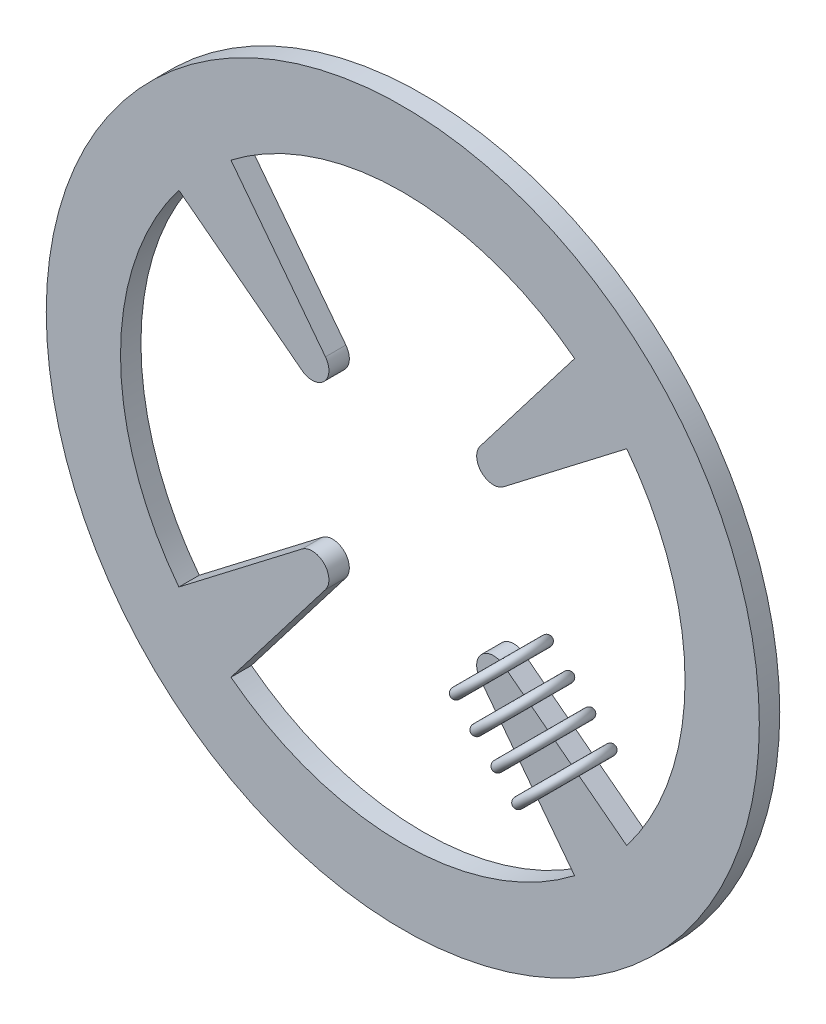
SolidWorks part; units mm, degrees
other "標示1"
sketch "草圖65"
ref_plane "前基準面" through (0, 0, 0) normal (0, 0, 1) x (1, 0, 0)
ref_plane "上基準面" through (0, 0, 0) normal (0, 1, 0) x (1, 0, 0)
ref_plane "右基準面" through (0, 0, 0) normal (1, 0, 0) x (0, 0, -1)
sketch "草圖1" plane through (0, 0, 0) normal (0, 0, 1) x (1, 0, 0)
  circle A0 centre (0, 0) radius 0.96
  circle A1 centre (0, 0) radius 0.76
extrude "填料-伸長1" add sketch "草圖1" along normal blind 0.055
sketch "草圖2" plane through (0, 0, 0.055) normal (0, 0, 1) x (1, 0, 0)
  line L0 (0, 0) -> (0, 1.565) construction
  line L1 (0, 0) -> (-1.8584, 0) construction
  line L2 (-0.0447, 0.3392) -> (-0.0992, 0.7535)
  line L3 (0.0447, 0.3392) -> (0.0992, 0.7535)
  line L4 (0.2714, 0.2082) -> (0.6029, 0.4627)
  line L5 (0.2082, 0.2714) -> (0.4627, 0.6029)
  line L6 (0.2082, -0.2714) -> (0.4627, -0.6029)
  line L7 (0.2714, -0.2082) -> (0.6029, -0.4627)
  line L8 (-0.2714, -0.2082) -> (-0.6029, -0.4627)
  line L9 (-0.2082, -0.2714) -> (-0.4627, -0.6029)
  line L10 (-0.2082, 0.2714) -> (-0.4627, 0.6029)
  line L11 (-0.2714, 0.2082) -> (-0.6029, 0.4627)
  circle A0 centre (0, 0) radius 0.3
  circle A1 centre (0, 0) radius 0.76 construction
  arc A3 (-0.0447, 0.3392) -> (0.0447, 0.3392) centre (0, 0.345) ccw
  arc A4 (0.0992, 0.7535) -> (-0.0992, 0.7535) centre (0, 0) ccw
  arc A5 (-0.76, 0) -> (0.76, 0) centre (0, 0) ccw
  arc A6 (0.6029, 0.4627) -> (0.4627, 0.6029) centre (0, 0) ccw
  arc A7 (0.2082, 0.2714) -> (0.2714, 0.2082) centre (0.244, 0.244) ccw
  arc A8 (0.4627, -0.6029) -> (0.6029, -0.4627) centre (0, 0) ccw
  arc A9 (0.2714, -0.2082) -> (0.2082, -0.2714) centre (0.244, -0.244) ccw
  arc A10 (-0.6029, -0.4627) -> (-0.4627, -0.6029) centre (0, 0) ccw
  arc A11 (-0.2082, -0.2714) -> (-0.2714, -0.2082) centre (-0.244, -0.244) ccw
  arc A12 (-0.4627, 0.6029) -> (-0.6029, 0.4627) centre (0, 0) ccw
  arc A13 (-0.2714, 0.2082) -> (-0.2082, 0.2714) centre (-0.244, 0.244) ccw
  point P23 (0, 0)
  point P34 (0, 0)
  point P41 (0, 0)
  circle M4 centre (0, 0) radius 0.76
  dimension "D1" = 7.5
  dimension "D3" = 2
  dimension "D4" = 4
  dimension "D2" = 7.5
extrude "填料-伸長2" add sketch "草圖2" against normal blind 0.055 contours L11 A13 L10 M4 | L5 A7 L4 M4 | L7 A9 L6 M4 | A11 L8 L9 M4
sketch "草圖7" plane through (0, 0, 0.055) normal (0, 0, 1) x (1, 0, 0)
  line L0 (0.2121, 0.2121) -> (0.2404, 0.2404) construction
  line L1 (0.2404, 0.2404) -> (0.2013, 0.2795) construction
  line L2 (0.2404, 0.2404) -> (0.5894, 0.5894) construction
  line L3 (0.0244, -0.0244) -> (-0.6648, 0.6648) construction
  line L4 (0.2404, -0.2404) -> (0.3328, -0.148)
  arc A0 (0.2082, 0.2714) -> (0.2714, 0.2082) centre (0.244, 0.244) ccw construction
  arc A1 (-0.2082, -0.2714) -> (-0.2714, -0.2082) centre (-0.244, -0.244) ccw construction
  arc A2 (-0.2714, 0.2082) -> (-0.2082, 0.2714) centre (-0.244, 0.244) ccw construction
  arc A3 (0.2714, -0.2082) -> (0.2082, -0.2714) centre (0.244, -0.244) ccw construction
  point P5 (0.297, 0.297)
  point P7 (-0.2121, -0.2121)
  point P8 (0.3536, 0.3536)
  point P9 (0.4101, 0.4101)
  point P12 (-0.2404, -0.2404)
  point P16 (-0.297, -0.297)
  point P17 (-0.3536, -0.3536)
  point P18 (-0.4101, -0.4101)
  point P20 (0.2404, -0.2404)
  point P21 (0, 0)
  point P23 (-0.2404, 0.2404)
  point P24 (-0.2121, 0.2121)
  point P25 (0.2121, -0.2121)
  point P29 (0.297, -0.297)
  point P33 (0.3536, -0.3536)
  point P34 (0.4101, -0.4101)
  point P35 (-0.297, 0.297)
  point P36 (-0.3536, 0.3536)
  point P37 (-0.4101, 0.4101)
  point P40 (0.4667, -0.4667)
  point P41 (0.5233, -0.5233)
  point P42 (0.4667, 0.4667)
  point P43 (0.5233, 0.5233)
  point P44 (-0.4667, 0.4667)
  point P45 (-0.5233, 0.5233)
  point P46 (-0.4667, -0.4667)
  point P47 (-0.5233, -0.5233)
  dimension "D1" = 0.08
  dimension "D2" = 0.08
  dimension "D3" = 0.08
  dimension "D4" = 0.04
  dimension "D5" = 0.04
  dimension "D6" = 0.08
  dimension "D7" = 0.08
  dimension "D8" = 0.08
  dimension "D9" = 0.04
  dimension "D10" = 0.04
  dimension "D11" = 0.08
  dimension "D12" = 0.08
  dimension "D13" = 0.08
  dimension "D14" = 0.08
  dimension "D15" = 0.08
  dimension "D16" = 0.08
  dimension "D17" = 0.08
  dimension "D18" = 0.08
  dimension "D19" = 0.08
  dimension "D20" = 0.08
  dimension "D21" = 0.08
  dimension "D22" = 0.08
  dimension "D23" = 0.08
  dimension "D24" = 0.08
ref_plane "平面5" through (0.2404, 0.2404, 0) normal (0.7071, 0.7071, 0) x (-0.7071, 0.7071, 0)
ref_plane "平面6" through (0.297, 0.297, 0) normal (0.7071, 0.7071, 0) x (0.7071, -0.7071, 0)
ref_plane "平面7" through (0.3536, 0.3536, 0) normal (0.7071, 0.7071, 0) x (0.7071, -0.7071, 0)
ref_plane "平面8" through (0.4101, 0.4101, 0) normal (0.7071, 0.7071, 0) x (0.7071, -0.7071, 0)
ref_plane "平面9" through (-0.2404, -0.2404, 0) normal (0.7071, 0.7071, 0) x (0.7071, -0.7071, 0)
ref_plane "平面10" through (-0.297, -0.297, 0) normal (0.7071, 0.7071, 0) x (0.7071, -0.7071, 0)
ref_plane "平面11" through (-0.3536, -0.3536, 0) normal (0.7071, 0.7071, 0) x (0.7071, -0.7071, 0)
ref_plane "平面12" through (-0.4101, -0.4101, 0) normal (0.7071, 0.7071, 0) x (0.7071, -0.7071, 0)
ref_plane "平面13" through (0.2404, -0.2404, 0) normal (0.7071, -0.7071, 0) x (0.7071, 0.7071, 0)
ref_plane "平面14" through (0.297, -0.297, 0) normal (0.7071, -0.7071, 0) x (0, 0, -1)
ref_plane "平面15" through (0.3536, -0.3536, 0) normal (0.7071, -0.7071, 0) x (0, 0, -1)
ref_plane "平面16" through (0.4101, -0.4101, 0) normal (0.7071, -0.7071, 0) x (0, 0, -1)
ref_plane "平面17" through (-0.2404, 0.2404, 0) normal (0.7071, -0.7071, 0) x (0, 0, -1)
ref_plane "平面18" through (-0.297, 0.297, 0) normal (0.7071, -0.7071, 0) x (0, 0, -1)
ref_plane "平面19" through (-0.3536, 0.3536, 0) normal (0.7071, -0.7071, 0) x (0, 0, -1)
ref_plane "平面20" through (-0.4101, 0.4101, 0) normal (0.7071, -0.7071, 0) x (0, 0, -1)
ref_plane "平面21" through (0, 0, 0) normal (-0.7071, -0.7071, 0) x (-0.7071, 0.7071, 0)
sketch "草圖68" plane through (0, 0, 0) normal (-0.7071, -0.7071, 0) x (-0.7071, 0.7071, 0)
  line L0 (-0.34, -0.0851) -> (-0.34, -0.3432)
  line L1 (-200000.0345, -0.055) -> (200000.9402, -0.055) construction
  circle A0 centre (-0.34, 0.025) radius 0.023
  point P1 (-0.34, 0.025)
  dimension "D1" = 0.08
sketch "草圖72" plane through (0.3536, -0.3536, 0) normal (0.7071, -0.7071, 0) x (0, 0, -1)
  line L0 (199999.9149, 0) -> (-200000.3432, 0) construction
  line L1 (-0.03, 0) -> (-0.03, 0.1)
  circle A0 centre (-0.03, 0) radius 0.1
  point P0 (-0.03, 0)
  point P8 (-0.03, 0.1)
  dimension "D1" = 0.025
ref_plane "平面24" through (0.4243, -0.2828, 0.03) normal (0, 0, 1) x (1, 0, 0)
sketch "草圖73" plane through (0.4243, -0.2828, 0.03) normal (0, 0, 1) x (1, 0, 0)
  circle A0 centre (0, 0) radius 0.0132
sweep "掃出2" add profiles "草圖73" path "草圖72"
sketch "草圖77" plane through (0.2404, -0.2404, 0) normal (0.7071, -0.7071, 0) x (0.7071, 0.7071, 0)
  line L0 (0, -199999.9149) -> (0, 200000.3432) construction
  line L1 (0.2556, 0.03) -> (-0.0556, 0.03) construction
  circle A0 centre (0, 0.03) radius 0.1
sketch "草圖79" plane through (0.2404, -0.2404, 0) normal (0.7071, -0.7071, 0) x (0.7071, 0.7071, 0)
  line L0 (0, 0.055) -> (0.1307, 0.055) construction
  point P0 (0.096, 0.055)
  point P1 (0.0781, 0.0935)
ref_plane "平面25" through (0.3083, -0.1725, 0.055) normal (-0.1781, -0.1781, 0.9678) x (0.984, -0.0322, 0.1752)
sketch "草圖82" plane through (0.3083, -0.1725, 0.055) normal (-0.1781, -0.1781, 0.9678) x (0.984, -0.0322, 0.1752)
  circle A0 centre (0, 0) radius 0.0132
sweep "掃出3" add profiles "草圖82" path "草圖77"
sketch "草圖83" plane through (0.297, -0.297, 0) normal (0.7071, -0.7071, 0) x (0, 0, -1)
  line L0 (199999.9149, 0) -> (-200000.3432, 0) construction
  line L1 (-0.0778, 0.1835) -> (-0.0322, 0.0086) construction
  line L2 (-0.03, 0) -> (-0.03, 0.1167)
  line L3 (-0.03, 0.1763) -> (-0.03, 0.0237) construction
  circle A0 centre (-0.03, 0) radius 0.1
  point P6 (-0.03, 0.1)
ref_plane "平面26" through (0.3677, -0.2263, 0.03) normal (0, 0, 1) x (1, 0, 0)
sketch "草圖84" plane through (0.3677, -0.2263, 0.03) normal (0, 0, 1) x (1, 0, 0)
  circle A0 centre (0, 0) radius 0.0132
sweep "掃出4" add profiles "草圖84" path "草圖83"
sketch "草圖85" plane through (0.4101, -0.4101, 0) normal (0.7071, -0.7071, 0) x (0, 0, -1)
  line L0 (199999.9149, 0) -> (-200000.3432, 0) construction
  line L1 (-0.03, 0) -> (-0.03, 0.1369)
  line L2 (-0.03, 0.1763) -> (-0.03, 0.0237) construction
  circle A0 centre (-0.03, 0) radius 0.1007
  point P5 (-0.03, 0.1007)
sketch "草圖86" plane through (0.4243, -0.2828, 0.03) normal (0, 0, 1) x (1, 0, 0)
  circle A0 centre (0.057, -0.0561) radius 0.0132
sweep "掃出5" add profiles "草圖86" path "草圖85"
